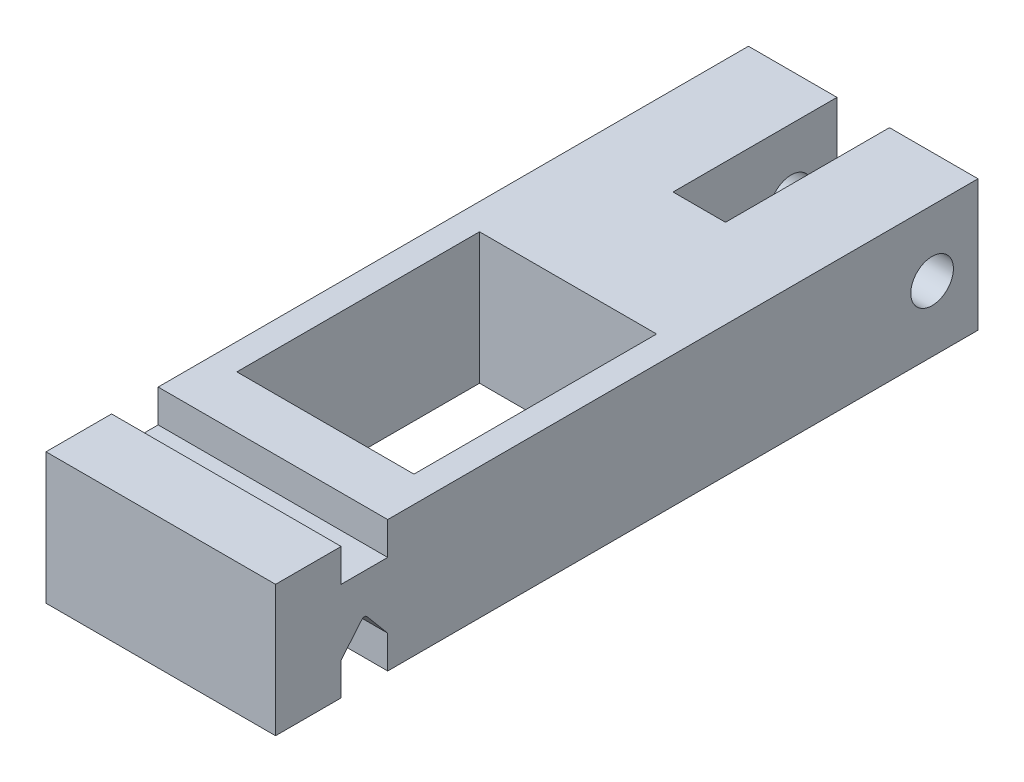
SolidWorks part; units mm, degrees
ref_plane "Alzado" through (0, 0, 0) normal (0, 0, 1) x (1, 0, 0)
ref_plane "Planta" through (0, 0, 0) normal (0, 1, 0) x (1, 0, 0)
ref_plane "Vista lateral" through (0, 0, 0) normal (1, 0, 0) x (0, 0, -1)
sketch "Croquis1" plane through (0, 0, 0) normal (1, 0, 0) x (0, 0, -1)
  line L8 (0, 10) -> (0, -10)
  line L9 (0, 0) -> (18.6556, 0) construction
  line L10 (10, -10) -> (10, -5)
  line L11 (0, 10) -> (10, 10)
  line L12 (10, 10) -> (10, 5)
  line L13 (10, 5) -> (17.1, 5)
  line L14 (17.1, 5) -> (17.1, 10)
  line L15 (17.1, 10) -> (107.1, 10)
  line L16 (107.1, 10) -> (107.1, -10)
  line L21 (10, -10) -> (0, -10)
  line L23 (17.1, -5) -> (17.1, -10)
  line L24 (17.1, -10) -> (107.1, -10)
  line L25 (10, -10) -> (17.1, -10) construction
  line L26 (107.1, 0) -> (100.1, 0) construction
  line L27 (17.1, -5) -> (13.55, -0.7693)
  line L28 (13.55, -0.7693) -> (10, -5)
  line L29 (13.55, -5) -> (13.55, -0.7693) construction
  line L30 (17.1, -5) -> (10, -5) construction
  circle A1 centre (100.1, 0) radius 3.25
  point P13 (13.5727, -5)
  point P19 (14.8069, -1.3962)
  point P20 (13.55, -2.0729)
  dimension "D6" = 6.5
  dimension "D1" = 20
  dimension "D2" = 10
  dimension "D3" = 5
  dimension "D4" = 7.1
  dimension "D5" = 90
  dimension "D7" = 7
  dimension "D8" = 50
extrude "Saliente-Extruir1" add sketch "Croquis1" along normal blind 35
sketch "Croquis2" plane through (0, 10, 0) normal (0, 1, 0) x (1, 0, 0)
  line L0 (21.5, 107.1) -> (21.5, 82.1)
  line L1 (35, 107.1) -> (0, 107.1) construction
  line L2 (21.5, 82.1) -> (13.5, 82.1)
  line L3 (13.5, 82.1) -> (13.5, 107.1)
  line L4 (13.5, 107.1) -> (21.5, 107.1)
  line L5 (17.5, 107.1) -> (17.5, 82.1) construction
  point P8 (14.1383, 80.239)
  point P9 (17.5, 81.3372)
  point P10 (0, 0)
  point P11 (0, 0)
  point P12 (15.5259, 72.1)
  dimension "D1" = 8
  dimension "D2" = 25
extrude "Cortar-Extruir1" cut sketch "Croquis2" against normal up to next
fillet "Redondeo1" radius 0.5 1 edges at (17.5, -0.7693, -13.55)
sketch "Croquis4" plane through (0, 10, 0) normal (0, 1, 0) x (1, 0, 0)
  line L0 (13.5, 82.1) -> (0, 82.1) construction
  line L5 (0, 107.1) -> (0, 17.1) construction
  line L6 (35, 17.1) -> (0, 17.1) construction
  line L7 (35, 107.1) -> (35, 17.1) construction
  line L8 (4, 25.1) -> (31, 25.1)
  line L9 (4, 25.1) -> (4, 62.1)
  line L10 (4, 62.1) -> (31, 62.1)
  line L11 (31, 25.1) -> (31, 62.1)
  line L12 (4, 25.1) -> (31, 62.1) construction
  line L13 (4, 62.1) -> (31, 25.1) construction
  line L14 (17.5, 82.1) -> (17.5, 43.6) construction
  line L15 (13.5, 82.1) -> (21.5, 82.1) construction
  point P5 (17.5, 43.6)
  dimension "D1" = 4
  dimension "D2" = 20
  dimension "D3" = 8
extrude "Cortar-Extruir2" cut sketch "Croquis4" against normal through all
